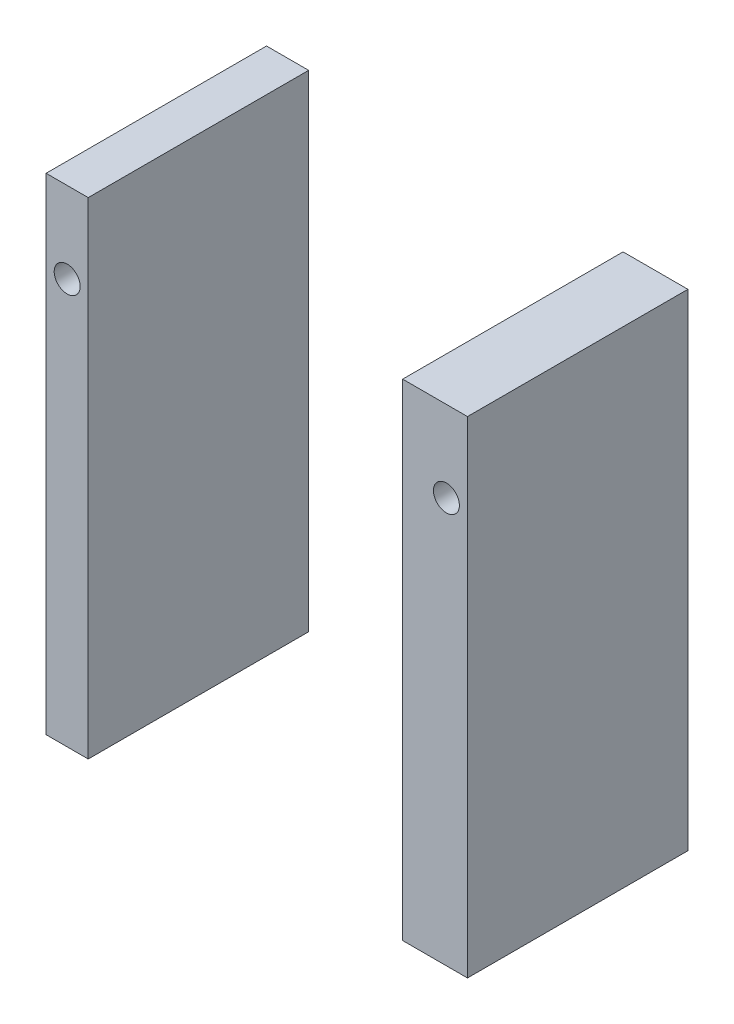
SolidWorks part; units mm, degrees
ref_plane "Front Plane" through (0, 0, 0) normal (0, 0, 1) x (1, 0, 0)
ref_plane "Top Plane" through (0, 0, 0) normal (0, 1, 0) x (1, 0, 0)
ref_plane "Right Plane" through (0, 0, 0) normal (1, 0, 0) x (0, 0, -1)
sketch "Sketch2" plane through (0, 0, 0) normal (0, 0, 1) x (1, 0, 0)
  line L0 (-16.51, 0) -> (16.51, 0) construction
  line L1 (-16.51, 38.1) -> (-13.208, 38.1)
  line L2 (-16.51, 38.1) -> (-16.51, 0)
  line L3 (-16.51, 0) -> (-13.208, 0)
  line L4 (-13.208, 38.1) -> (-13.208, 0)
  line L5 (11.43, 38.1) -> (16.51, 38.1)
  line L6 (11.43, 38.1) -> (11.43, 0)
  line L7 (11.43, 0) -> (16.51, 0)
  line L8 (16.51, 38.1) -> (16.51, 0)
  point P5 (41.4981, -0.3089)
  point P10 (0, 0)
  point P11 (0, 0)
  point P13 (0, 0)
  dimension "D1" = 38.1
  dimension "D2" = 3.302
  dimension "D3" = 24.638
  dimension "D4" = 5.08
extrude "Boss-Extrude1" add sketch "Sketch2" along normal blind 17.272
sketch "Sketch3" plane through (0, 0, 17.272) normal (0, 0, 1) x (1, 0, 0)
  line L0 (-16.51, 0) -> (-13.208, 0) construction
  line L1 (11.43, 0) -> (16.51, 0) construction
  line L2 (-14.859, 31.75) -> (-16.51, 31.75) construction
  line L3 (-16.51, 38.1) -> (-16.51, 0) construction
  line L4 (14.859, 31.75) -> (16.51, 31.75) construction
  line L5 (16.51, 0) -> (16.51, 38.1) construction
  line L6 (-14.859, 31.75) -> (14.859, 31.75) construction
  circle A0 centre (-14.859, 31.75) radius 1.016
  circle A1 centre (14.859, 31.75) radius 1.016
  dimension "D1" = 2.032
  dimension "D2" = 2.032
  dimension "D3" = 31.75
  dimension "D4" = 31.75
  dimension "D5" = 1.651
  dimension "D6" = 1.651
extrude "Cut-Extrude1" cut sketch "Sketch3" against normal blind 2.032
